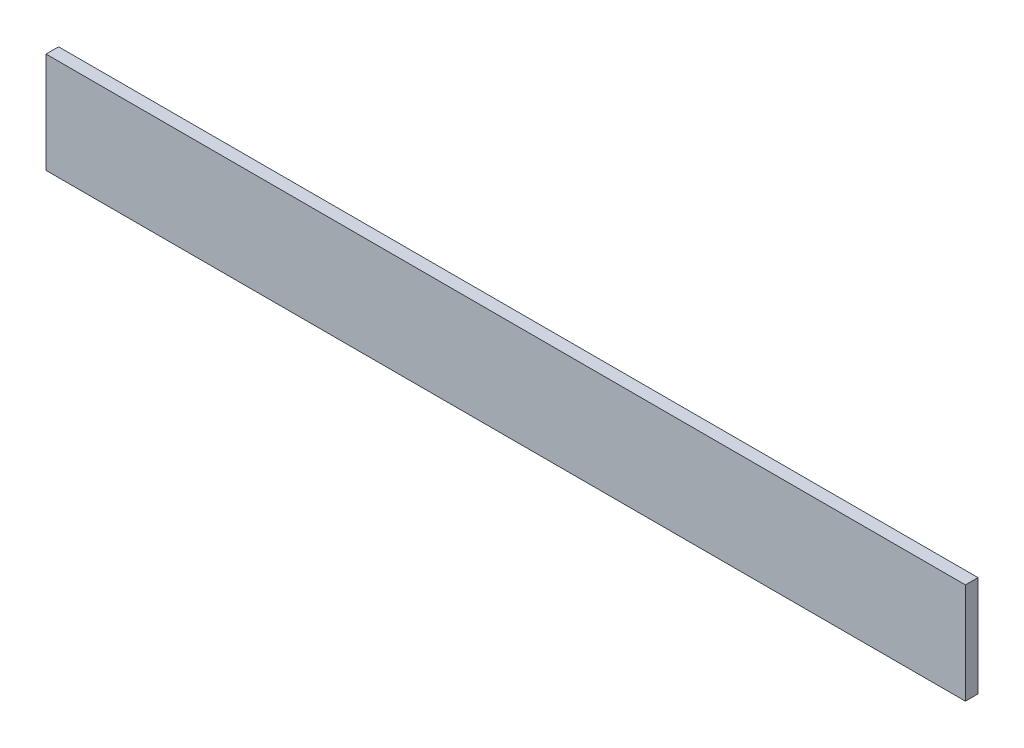
SolidWorks part; units mm, degrees
ref_plane "Plan de face" through (0, 0, 0) normal (0, 0, 1) x (1, 0, 0)
ref_plane "Plan de dessus" through (0, 0, 0) normal (0, 1, 0) x (1, 0, 0)
ref_plane "Plan de droite" through (0, 0, 0) normal (1, 0, 0) x (0, 0, -1)
sketch "Esquisse1" plane through (0, 0, 0) normal (0, 0, 1) x (1, 0, 0)
  line L1 (-182.5, 20) -> (182.5, 20)
  line L2 (-182.5, 20) -> (-182.5, -20)
  line L3 (-182.5, -20) -> (182.5, -20)
  line L4 (182.5, 20) -> (182.5, -20)
  line L5 (-182.5, 20) -> (182.5, -20) construction
  line L6 (-182.5, -20) -> (182.5, 20) construction
  point P0 (0, 0)
  dimension "D1" = 365
  dimension "D2" = 40
extrude "Boss.-Extru.1" add sketch "Esquisse1" along normal blind 5
